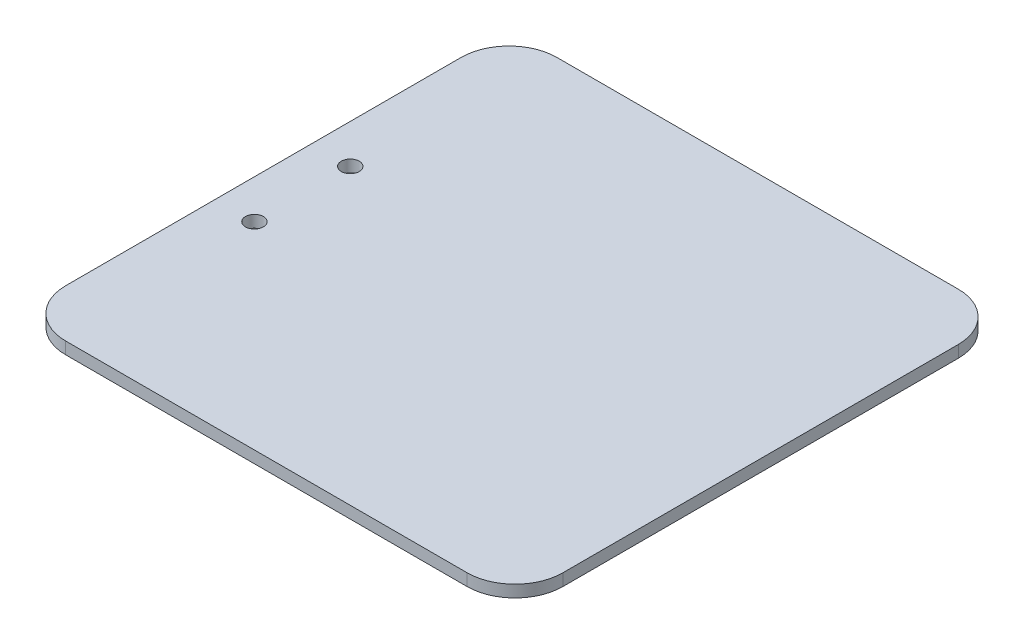
SolidWorks part; units mm, degrees
ref_plane "Front Plane" through (0, 0, 0) normal (0, 0, 1) x (1, 0, 0)
ref_plane "Top Plane" through (0, 0, 0) normal (0, 1, 0) x (1, 0, 0)
ref_plane "Right Plane" through (0, 0, 0) normal (1, 0, 0) x (0, 0, -1)
sketch "Sketch1" plane through (0, 0, 0) normal (0, 1, 0) x (1, 0, 0)
  line L0 (0, 41) -> (83, 41) construction
  line L1 (8, 0) -> (75, 0)
  line L2 (0, 8) -> (0, 74)
  line L3 (8, 82) -> (75, 82)
  line L4 (83, 8) -> (83, 74)
  circle A0 centre (6.5, 49) radius 1.5
  circle A1 centre (6.5, 33) radius 1.5
  arc A2 (8, 0) -> (0, 8) centre (8, 8) cw
  arc A3 (75, 0) -> (83, 8) centre (75, 8) ccw
  arc A4 (75, 82) -> (83, 74) centre (75, 74) cw
  arc A5 (0, 74) -> (8, 82) centre (8, 74) cw
  point P13 (0, 0)
  point P16 (83, 0)
  point P21 (0, 82)
  dimension "D3" = 3
  dimension "D6" = 8
  dimension "D1" = 83
  dimension "D2" = 82
  dimension "D4" = 8
  dimension "D5" = 6.5
extrude "Boss-Extrude1" add sketch "Sketch1" along normal blind 2
